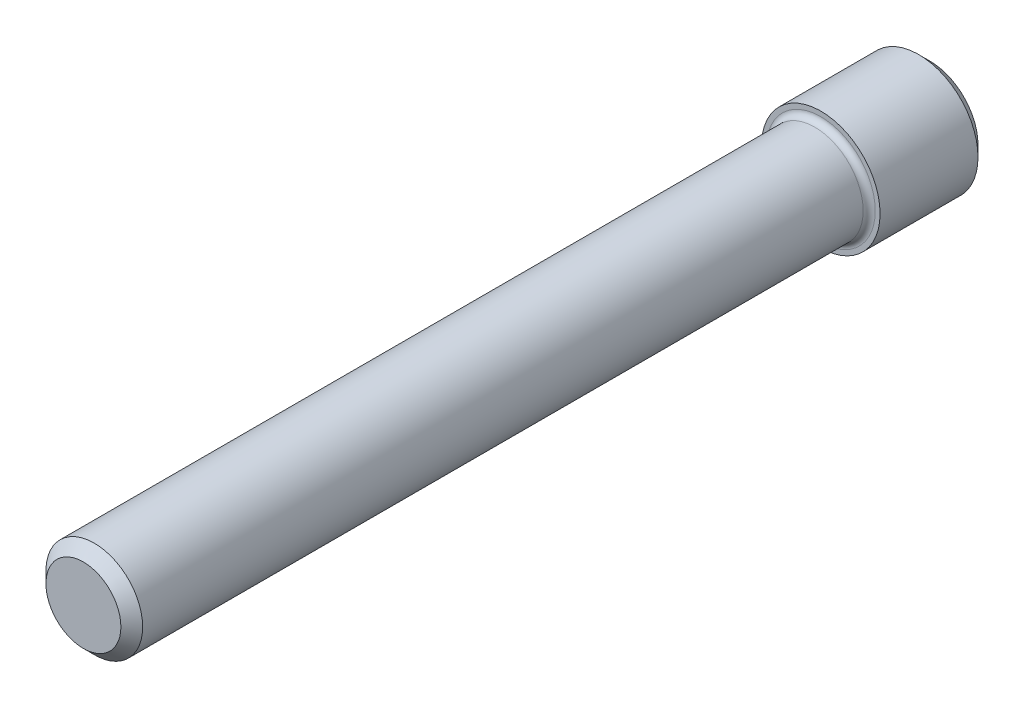
SolidWorks part; units mm, degrees
material "Malleable Cast Iron"
ref_plane "Front Plane" through (0, 0, 0) normal (0, 0, 1) x (1, 0, 0)
ref_plane "Top Plane" through (0, 0, 0) normal (0, 1, 0) x (1, 0, 0)
ref_plane "Right Plane" through (0, 0, 0) normal (1, 0, 0) x (0, 0, -1)
sketch "Sketch1" plane through (0, 0, 0) normal (1, 0, 0) x (0, 0, -1)
  line L0 (0, 0) -> (70, 0) construction
  line L1 (0, 0) -> (0, 3.1)
  line L2 (0.9, 4) -> (60.5, 4)
  line L3 (61, 4.5) -> (61, 4.9)
  line L4 (61, 4.9) -> (69.1, 4.9)
  line L5 (69.1, 4.9) -> (70, 4)
  line L6 (70, 4) -> (70, 0)
  line L7 (0, 0) -> (0, 4) construction
  line L8 (0, 3.1) -> (0.9, 4)
  line L9 (70, 4) -> (70, 5.3271) construction
  line L10 (0, 0) -> (70, 0)
  arc A0 (60.5, 4) -> (61, 4.5) centre (60.5, 4.5) ccw
  point P14 (61, 4)
  dimension "D3" = 0.5
  dimension "D1" = 9
  dimension "D2" = 70
  dimension "D4" = 4
  dimension "D5" = 4.9
  dimension "D6" = 0.9
  dimension "D7" = 45
  dimension "D8" = 45
  dimension "D9" = 0.9
revolve "Revolve1" add sketch "Sketch1" angle 360 about L10
